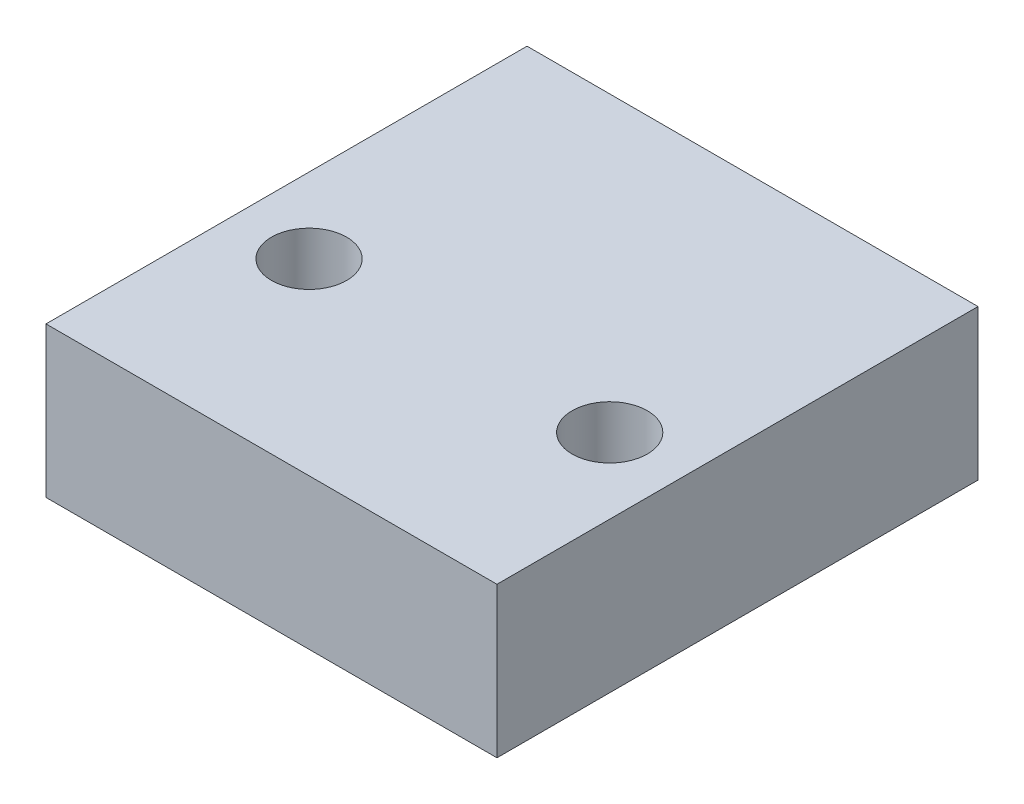
SolidWorks part; units mm, degrees
ref_plane "Front Plane" through (0, 0, 0) normal (0, 0, 1) x (1, 0, 0)
ref_plane "Top Plane" through (0, 0, 0) normal (0, 1, 0) x (1, 0, 0)
ref_plane "Right Plane" through (0, 0, 0) normal (1, 0, 0) x (0, 0, -1)
sketch "Sketch1" plane through (0, 0, 0) normal (0, 1, 0) x (1, 0, 0)
  line L0 (-12.5, -2.5) -> (-12.5, 2.5) construction
  line L1 (-15, 14.5) -> (15, 14.5) construction
  line L2 (-15, 14.5) -> (-15, -7.5) construction
  line L3 (-15, -7.5) -> (15, -7.5) construction
  line L4 (15, 14.5) -> (15, -7.5) construction
  line L5 (-7.5, -2.5) -> (-7.5, 2.5) construction
  line L6 (7.5, -2.5) -> (7.5, 2.5) construction
  line L7 (12.5, -2.5) -> (12.5, 2.5) construction
  line L8 (-10, 5) -> (-10, 2.5) construction
  line L9 (-10, 2.5) -> (-10, -2.5) construction
  line L10 (-10, -2.5) -> (-10, -5) construction
  line L11 (-10, 0) -> (-7.5, 0) construction
  line L12 (-7.5, 0) -> (0, 0) construction
  line L13 (0, 0) -> (7.5, 0) construction
  line L14 (-10, 2.5) -> (10, 2.5) construction
  line L15 (-15, 7.5) -> (15, 7.5) construction
  line L16 (-10, -2.5) -> (10, -2.5) construction
  line L17 (0, 0) -> (0, -7.5) construction
  line L18 (0, 0) -> (0, 7.5) construction
  line L20 (-15, 19.5) -> (15, 19.5)
  line L21 (-15, 19.5) -> (-15, -12.5)
  line L22 (-15, -12.5) -> (15, -12.5)
  line L23 (15, 19.5) -> (15, -12.5)
  circle A0 centre (-10, 2.5) radius 2.5 construction
  circle A1 centre (-10, -2.5) radius 2.5 construction
  circle A2 centre (10, 2.5) radius 2.5 construction
  circle A3 centre (10, -2.5) radius 2.5 construction
  circle A4 centre (-10, 0) radius 2.5
  circle A5 centre (10, 0) radius 2.5
  dimension "D1" = 22
  dimension "D2" = 30
  dimension "D3" = 7
  dimension "D4" = 15
  dimension "D5" = 5
  dimension "D6" = 10
  dimension "D7" = 5
  dimension "D8" = 5
extrude "Boss-Extrude1" add sketch "Sketch1" along normal blind 10 contours L4 L1 L2 L3 A3 L6 A2 L7 A1 L0 A0 L5 | L23 L20 L21 L22 A5 A4
